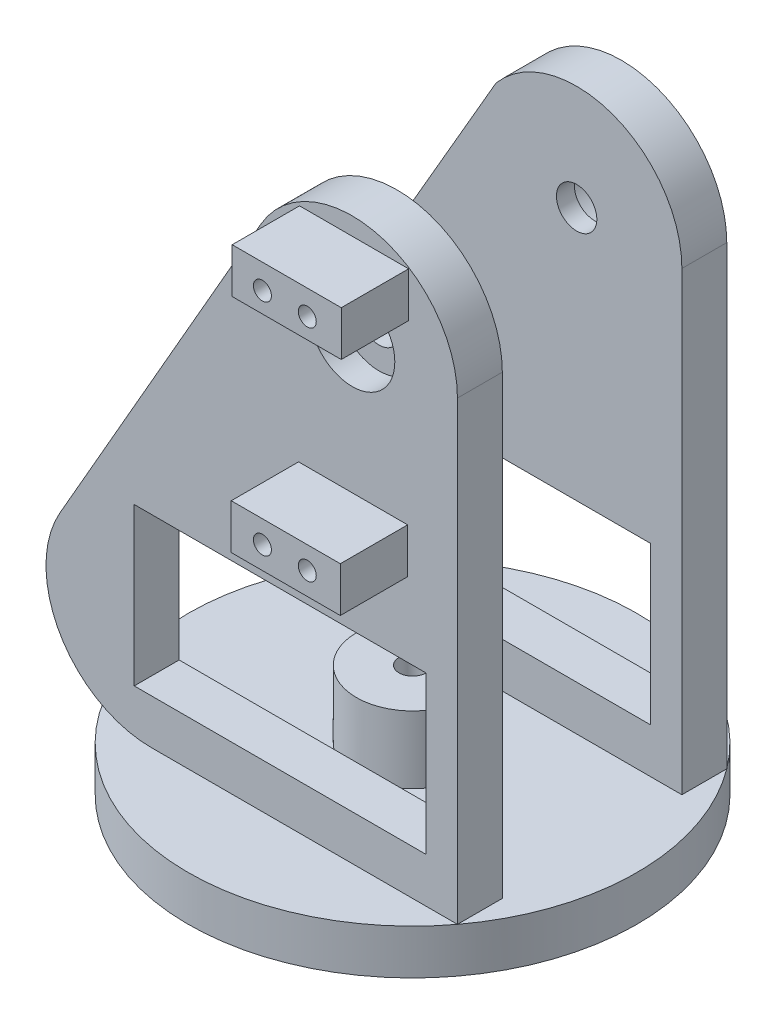
SolidWorks part; units mm, degrees
ref_plane "Front Plane" through (0, 0, 0) normal (0, 0, 1) x (1, 0, 0)
ref_plane "Top Plane" through (0, 0, 0) normal (0, 1, 0) x (1, 0, 0)
ref_plane "Right Plane" through (0, 0, 0) normal (1, 0, 0) x (0, 0, -1)
sketch "Sketch1" plane through (0, 0, 0) normal (0, 0, 1) x (1, 0, 0)
  line L10 (-144.5903, 91.8409) -> (-99.8308, 169.9215)
  line L16 (-124.246, 56.7285) -> (-79.246, 56.7285)
  line L20 (-79.4864, 56.7285) -> (-56.0364, 56.7285)
  line L21 (-56.0364, 158.2591) -> (-56.0364, 56.7285)
  arc A0 (-56.0364, 158.2591) -> (-99.8308, 169.9215) centre (-79.4864, 158.2591) ccw
  arc A1 (-144.5903, 91.8409) -> (-124.246, 56.7285) centre (-124.246, 80.1785) ccw
extrude "Boss-Extrude2" add sketch "Sketch1" along normal blind 10
sketch "Sketch2" plane through (0, 0, 10) normal (0, 0, 1) x (1, 0, 0)
  circle A0 centre (-79.4864, 158.2591) radius 4.5
  dimension "D1" = 9
extrude "Cut-Extrude2" cut sketch "Sketch2" against normal up to next
sketch "Sketch3" plane through (0, 0, 10) normal (0, 0, 1) x (1, 0, 0)
  circle A0 centre (-79.4864, 158.2591) radius 9.5
  dimension "D1" = 19
extrude "Cut-Extrude3" cut sketch "Sketch3" against normal blind 6 contours A0
sketch "Sketch4" plane through (0, 0, 10) normal (0, 0, 1) x (1, 0, 0)
sketch "Sketch6" plane through (0, 0, 10) normal (0, 0, 1) x (1, 0, 0)
  line L0 (-91.4284, 128.2591) -> (-67.1292, 128.2591)
  line L1 (-91.2145, 177.7591) -> (-66.9153, 177.7591)
  line L2 (-91.2145, 177.7591) -> (-91.2145, 167.7591)
  line L3 (-91.2145, 167.7591) -> (-66.9153, 167.7591)
  line L4 (-66.9153, 177.7591) -> (-66.9153, 167.7591)
  line L5 (-91.4284, 128.2591) -> (-91.4284, 118.2591)
  line L6 (-91.4284, 118.2591) -> (-67.1292, 118.2591)
  line L7 (-67.1292, 128.2591) -> (-67.1292, 118.2591)
  point P8 (-79.4864, 158.2591)
  dimension "D1" = 30
  dimension "D2" = 10
  dimension "D3" = 10
  dimension "D4" = 9.5
sketch "Sketch5" plane through (0, 0, 10) normal (0, 0, 1) x (1, 0, 0)
  line L0 (-79.4864, 158.2591) -> (-79.4864, 172.2591)
  line L1 (-79.4864, 172.2591) -> (-74.4864, 172.2591)
  line L2 (-79.4864, 172.2591) -> (-84.4864, 172.2591)
  line L3 (-79.4864, 158.2591) -> (-79.4864, 123.2591)
  line L4 (-79.4864, 123.2591) -> (-74.4864, 123.2591)
  line L5 (-79.4864, 123.2591) -> (-84.4864, 123.2591)
  circle A0 centre (-84.4864, 172.2591) radius 2
  circle A1 centre (-74.4864, 172.2591) radius 2
  circle A2 centre (-84.4864, 123.2591) radius 2
  circle A3 centre (-74.4864, 123.2591) radius 2
  dimension "D1" = 4
  dimension "D2" = 4
  dimension "D3" = 4
  dimension "D4" = 4
  dimension "D5" = 14
  dimension "D6" = 35
  dimension "D7" = 5
extrude "Boss-Extrude7" add sketch "Sketch6" along normal blind 15
extrude "Cut-Extrude5" cut sketch "Sketch5" against normal blind 10 and the other way blind 15 contours A2 | A3 | A1 | A0
sketch "Sketch10" plane through (0, 0, 10) normal (0, 0, 1) x (1, 0, 0)
  line L0 (-56.0364, 158.2591) -> (-56.0364, 56.7285) construction
  line L1 (-128.0364, 101.7285) -> (-63.0364, 101.7285)
  line L2 (-128.0364, 101.7285) -> (-128.0364, 66.7285)
  line L3 (-128.0364, 66.7285) -> (-63.0364, 66.7285)
  line L4 (-63.0364, 101.7285) -> (-63.0364, 66.7285)
  line L5 (-128.0364, 101.7285) -> (-63.0364, 66.7285) construction
  line L6 (-128.0364, 66.7285) -> (-63.0364, 101.7285) construction
  line L7 (-124.246, 56.7285) -> (-56.0364, 56.7285) construction
  point P0 (-95.5364, 84.2285)
  dimension "D1" = 65
  dimension "D2" = 35
  dimension "D3" = 7
  dimension "D4" = 10
extrude "Cut-Extrude6" cut sketch "Sketch10" against normal through all contours L2 L1 L4 L3
ref_plane "Plane2" through (0, 0, -40) normal (0, 0, -1) x (-1, 0, 0)
sketch "Sketch11" plane through (0, 0, -40) normal (0, 0, -1) x (-1, 0, 0)
  line L0 (56.0364, 56.7285) -> (56.0364, 158.2591)
  line L1 (97.4421, 173.3421) -> (144.5903, 91.8409)
  line L2 (124.246, 56.7285) -> (56.0364, 56.7285)
  line L3 (63.0364, 66.7285) -> (63.0364, 101.7285)
  line L4 (63.0364, 101.7285) -> (128.0364, 101.7285)
  line L5 (128.0364, 101.7285) -> (128.0364, 66.7285)
  line L6 (128.0364, 66.7285) -> (63.0364, 66.7285)
  arc A0 (56.0364, 158.2591) -> (97.4421, 173.3421) centre (79.4864, 158.2591) cw
  arc A1 (99.8308, 169.9215) -> (56.0364, 158.2591) centre (79.4864, 158.2591) ccw construction
  arc A2 (144.5903, 91.8409) -> (124.246, 56.7285) centre (124.3382, 80.1251) cw
  circle A3 centre (79.4864, 158.2591) radius 4.5
  dimension "D1" = 9
extrude "Boss-Extrude8" add sketch "Sketch11" along normal blind 10 separate body
sketch "Sketch12" plane through (0, 56.7285, 0) normal (0, -1, 0) x (1, 0, 0)
  line L0 (-56.0364, -20) -> (-155.9281, -20) construction
  line L1 (-56.0364, 0) -> (-56.0364, -40) construction
  circle A0 centre (-96.0364, -20) radius 50
  dimension "D2" = 100
  dimension "D1" = 20
  dimension "D3" = 40
extrude "Boss-Extrude9" add sketch "Sketch12" along normal blind 10
sketch "Sketch13" plane through (0, 56.7285, 0) normal (0, 1, 0) x (1, 0, 0)
  circle A0 centre (-96.0364, 20) radius 3
  point P0 (-96.0364, 20)
  dimension "D1" = 6
extrude "Cut-Extrude7" cut sketch "Sketch13" against normal blind 10
sketch "Sketch14" plane through (0, 56.7285, 0) normal (0, 1, 0) x (1, 0, 0)
  circle A0 centre (-96.0364, 20) radius 12.5
  circle A1 centre (-96.0364, 20) radius 3
  dimension "D1" = 25
extrude "Boss-Extrude10" add sketch "Sketch14" along normal blind 15
sketch "Sketch15" plane through (0, 0, -50) normal (0, 0, -1) x (-1, 0, 0)
  circle A0 centre (79.4864, 158.2591) radius 9.5
  dimension "D1" = 19
extrude "Cut-Extrude8" cut sketch "Sketch15" against normal blind 6
equation "\"D2@Sketch5\"=\"D1@Sketch5\""
equation "\"D3@Sketch5\"=\"D1@Sketch5\""
equation "\"D4@Sketch5\"=\"D1@Sketch5\""
